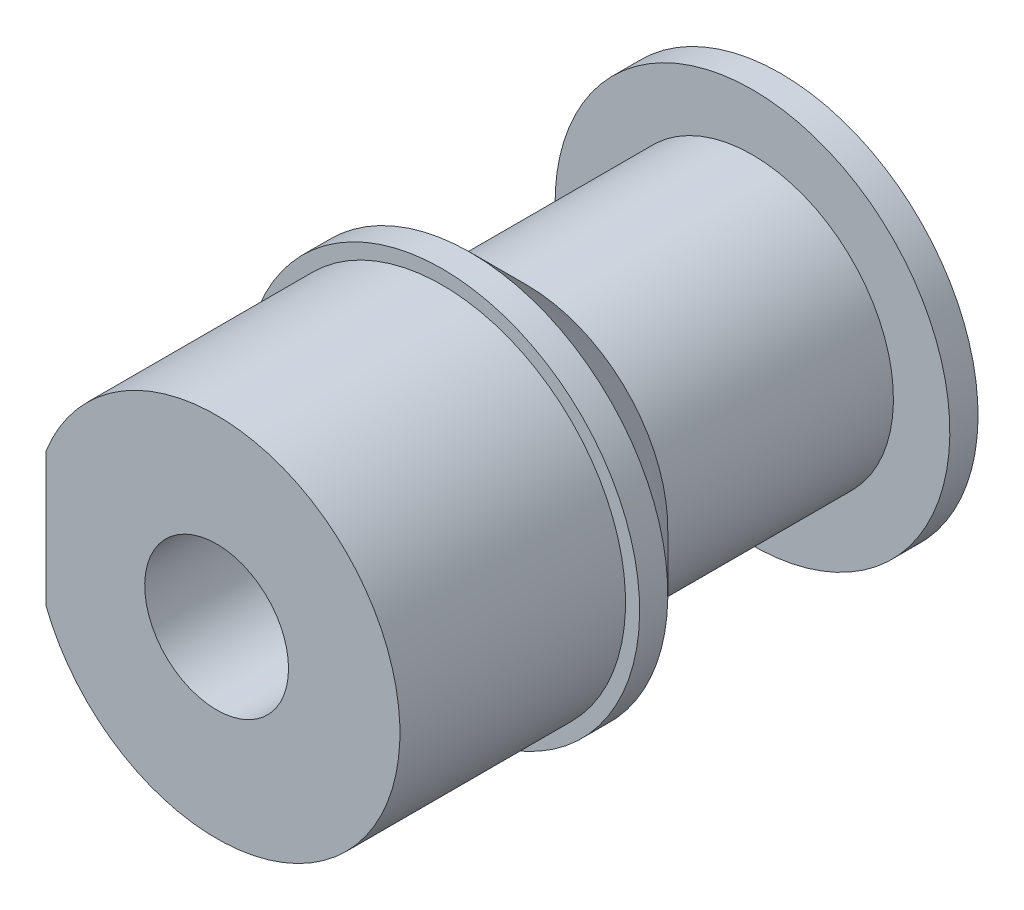
SolidWorks part; units mm, degrees
ref_plane "Front Plane" through (0, 0, 0) normal (0, 0, 1) x (1, 0, 0)
ref_plane "Top Plane" through (0, 0, 0) normal (0, 1, 0) x (1, 0, 0)
ref_plane "Right Plane" through (0, 0, 0) normal (1, 0, 0) x (0, 0, -1)
sketch "Sketch1" plane through (0, 0, 0) normal (0, 0, 1) x (1, 0, 0)
  line L0 (-2, 1.5) -> (-2, -1.5) construction
  line L1 (-2.05, 1.5166) -> (-2.05, -1.5166)
  arc A0 (-2, -1.5) -> (-2, 1.5) centre (0, 0) ccw construction
  arc A1 (-2.05, -1.5166) -> (-2.05, 1.5166) centre (0, 0) ccw
  point P1 (2.5, 0)
  dimension "D1" = 2.5
  dimension "D2" = 4.5
  dimension "D3" = 0.05
sketch "Sketch2" plane through (0, 0, 0) normal (1, 0, 0) x (0, 0, -1)
  line L0 (0, 0) -> (-20, 0)
  line L2 (-12, 7) -> (-11, 7)
  line L3 (-11, 7) -> (-9, 5)
  line L4 (-9, 5) -> (-1, 5)
  line L5 (-1, 5) -> (-1, 7)
  line L6 (-1, 7) -> (0, 7)
  line L7 (0, 7) -> (0, 0)
  line L8 (-12, 7) -> (-12, 6.5)
  line L9 (-12, 6.5) -> (-20, 6.5)
  line L10 (-20, 6.5) -> (-20, 0)
  dimension "D1" = 2
  dimension "D2" = 45
  dimension "D3" = 5
  dimension "D4" = 6.5
  dimension "D5" = 8
  dimension "D6" = 1
  dimension "D7" = 20
revolve "Revolve1" add sketch "Sketch2" angle 360 about L0
extrude "Cut-Extrude1" cut sketch "Sketch1" against normal through all and the other way through all
sketch "Sketch3" plane through (0, 0, 20) normal (0, 0, 1) x (1, 0, 0)
  line L0 (-6.05, -2.3764) -> (-6.05, 2.3764)
  line L1 (-2.05, 1.5166) -> (-2.05, -1.5166) construction
  circle A0 centre (0, 0) radius 6.5 construction
  circle A1 centre (0, 0) radius 6.5 construction
  arc A2 (-6.05, -2.3764) -> (-6.05, 2.3764) centre (0, 0) cw
  dimension "D1" = 4
extrude "Cut-Extrude2" cut sketch "Sketch3" against normal up to surface (8 mm away) up to face at (0, 6.5, 12)
sketch "Sketch4" plane through (-6.05, 0, 0) normal (-1, 0, 0) x (0, 0, 1)
  line L1 (12, 2.3764) -> (12, -2.3764) construction
  circle A0 centre (14.3, 0) radius 1.9
  point P0 (12.4, 0)
  point P6 (12, 0)
  dimension "D1" = 3.8
  dimension "D2" = 0.4
extrude "Cut-Extrude3" cut sketch "Sketch4" against normal up to next
sketch "Sketch5" plane through (0, 0, 20) normal (0, 0, 1) x (1, 0, 0)
  circle A0 centre (0, 0) radius 2.55
extrude "Cut-Extrude4" cut sketch "Sketch5" against normal up to vertex (5.7 mm away) up to point (-6.05, 0, 14.3)
